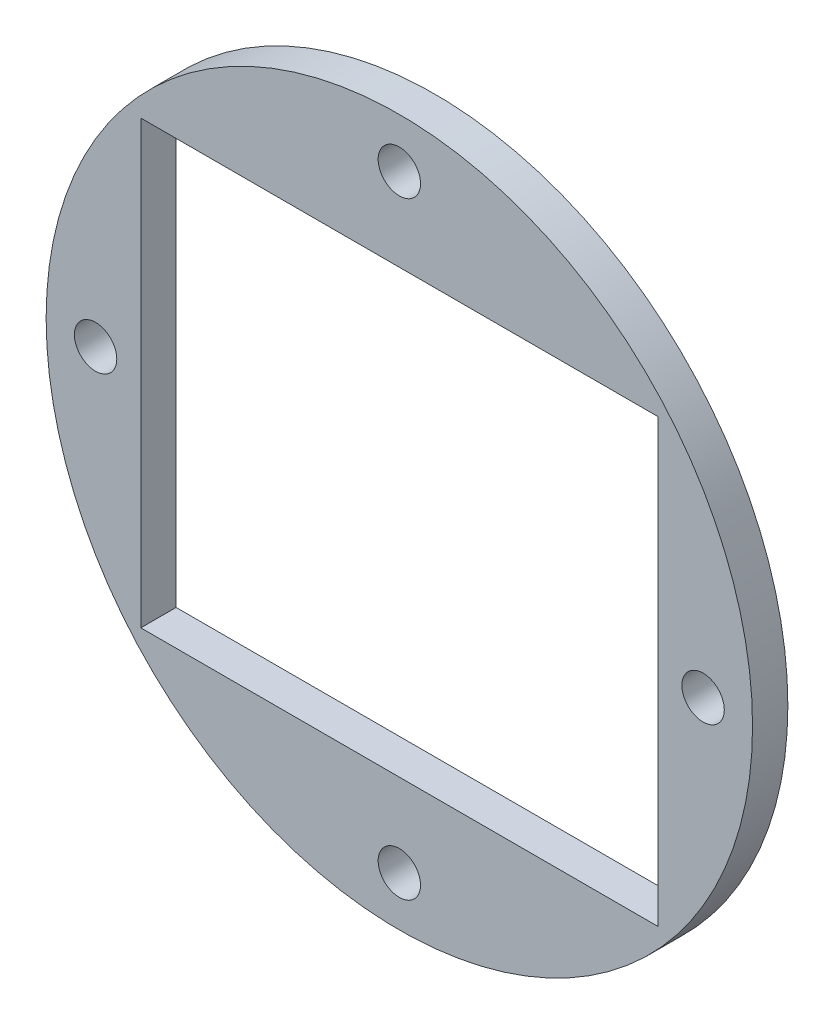
SolidWorks part; units mm, degrees
ref_plane "Plan de face" through (0, 0, 0) normal (0, 0, 1) x (1, 0, 0)
ref_plane "Plan de dessus" through (0, 0, 0) normal (0, 1, 0) x (1, 0, 0)
ref_plane "Plan de droite" through (0, 0, 0) normal (1, 0, 0) x (0, 0, -1)
sketch "Esquisse1" plane through (0, 0, 0) normal (0, 0, 1) x (1, 0, 0)
  line L0 (-36.6, 31.25) -> (36.6, -31.25) construction
  line L1 (-36.6, 31.25) -> (36.6, 31.25)
  line L2 (-36.6, 31.25) -> (-36.6, -31.25)
  line L3 (-36.6, -31.25) -> (36.6, -31.25)
  line L4 (36.6, 31.25) -> (36.6, -31.25)
  line L5 (36.6, 31.25) -> (-36.6, -31.25) construction
  line L6 (-61.4, 0) -> (68.8, 0) construction
  line L7 (0, 58.5) -> (0, -60.5) construction
  circle A0 centre (0, 0) radius 50
  circle A1 centre (43, 0) radius 3
  circle A2 centre (0, 43) radius 3
  circle A3 centre (-43, 0) radius 3
  circle A4 centre (0, -43) radius 3
  point P4 (0, 0)
  dimension "D3" = 100
  dimension "D6" = 6
  dimension "D1" = 73.2
  dimension "D2" = 62.5
  dimension "D4" = 43
  dimension "D5" = 43
extrude "Boss.-Extru.1" add sketch "Esquisse1" along normal blind 5
